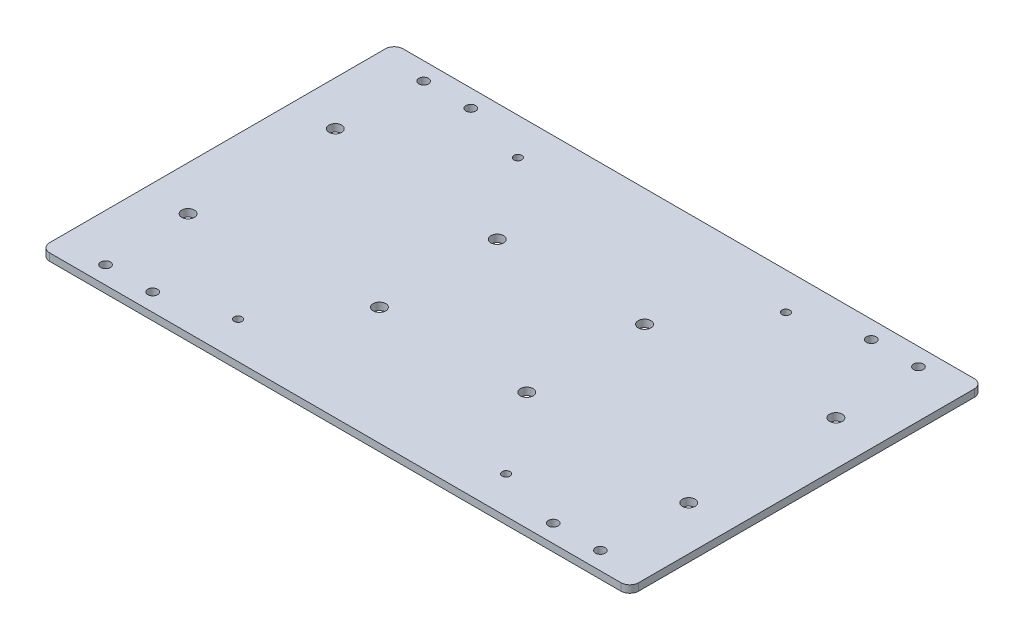
SolidWorks part; units mm, degrees
ref_plane "前基準面" through (0, 0, 0) normal (0, 0, 1) x (1, 0, 0)
ref_plane "上基準面" through (0, 0, 0) normal (0, 1, 0) x (1, 0, 0)
ref_plane "右基準面" through (0, 0, 0) normal (1, 0, 0) x (0, 0, -1)
sketch "草圖1" plane through (0, 0, 0) normal (0, 1, 0) x (1, 0, 0)
  line L0 (0, -55) -> (0, 55) construction
  line L1 (-100, 60) -> (100, 60)
  line L2 (-100, 60) -> (-100, -60)
  line L3 (-100, -60) -> (100, -60)
  line L4 (100, 60) -> (100, -60)
  line L5 (-55, 0) -> (55, 0) construction
  line L6 (85, 25) -> (85, -25) construction
  line L7 (-25, 20) -> (25, 20) construction
  line L8 (-25, 20) -> (-25, -20) construction
  line L9 (-25, -20) -> (25, -20) construction
  line L10 (25, 20) -> (25, -20) construction
  line L11 (-85, 25) -> (-85, -25) construction
  circle A0 centre (-84, 54) radius 1.65
  circle A1 centre (-68, 54) radius 1.65
  circle A8 centre (68, 54) radius 1.65
  circle A9 centre (84, 54) radius 1.65
  circle A10 centre (84, -54) radius 1.65
  circle A11 centre (68, -54) radius 1.65
  circle A12 centre (-68, -54) radius 1.65
  circle A13 centre (-84, -54) radius 1.65
  circle A14 centre (25, 20) radius 2.15
  circle A15 centre (-25, 20) radius 2.15
  circle A16 centre (-25, -20) radius 2.15
  circle A17 centre (25, -20) radius 2.15
  circle A18 centre (85, 25) radius 2.15
  circle A19 centre (85, -25) radius 2.15
  circle A20 centre (-85, -25) radius 2.15
  circle A21 centre (-85, 25) radius 2.15
  dimension "D5" = 3.3
  dimension "D8" = 3.3
  dimension "D16" = 4.3
  dimension "D17" = 4.3
  dimension "D18" = 4.3
  dimension "D19" = 4.3
  dimension "D23" = 4.3
  dimension "D24" = 4.3
  dimension "D1" = 200
  dimension "D2" = 100
  dimension "D3" = 120
  dimension "D4" = 60
  dimension "D6" = 6
  dimension "D7" = 68
  dimension "D9" = 6
  dimension "D10" = 16
  dimension "D12" = 40
  dimension "D13" = 20
  dimension "D14" = 50
  dimension "D15" = 25
  dimension "D20" = 50
  dimension "D21" = 25
  dimension "D22" = 60
  dimension "D11" = 2
extrude "填料-伸長2" add sketch "草圖1" along normal blind 2.5
sketch "草圖2" plane through (0, 2.5, 0) normal (0, 1, 0) x (1, 0, 0)
  line L0 (0, -1.375) -> (0, 1.375) construction
  line L1 (-45.5, 47.5) -> (45.5, 47.5) construction
  line L2 (-45.5, 47.5) -> (-45.5, -47.5) construction
  line L3 (-45.5, -47.5) -> (45.5, -47.5) construction
  line L4 (45.5, 47.5) -> (45.5, -47.5) construction
  line L5 (-1.375, 0) -> (1.375, 0) construction
  circle A0 centre (-45.5, 47.5) radius 1.35
  circle A1 centre (45.5, 47.5) radius 1.35
  circle A2 centre (-45.5, -47.5) radius 1.35
  circle A3 centre (45.5, -47.5) radius 1.35
  dimension "D5" = 2.7
  dimension "D6" = 2.7
  dimension "D7" = 2.7
  dimension "D8" = 2.7
  dimension "D1" = 91
  dimension "D2" = 45.5
  dimension "D3" = 95
  dimension "D4" = 47.5
extrude "除料-伸長1" cut sketch "草圖2" against normal up to next
fillet "圓角1" radius 3 4 edges at (-100, 1.25, 60) (100, 1.25, 60) (100, 1.25, -60) (-100, 1.25, -60)
